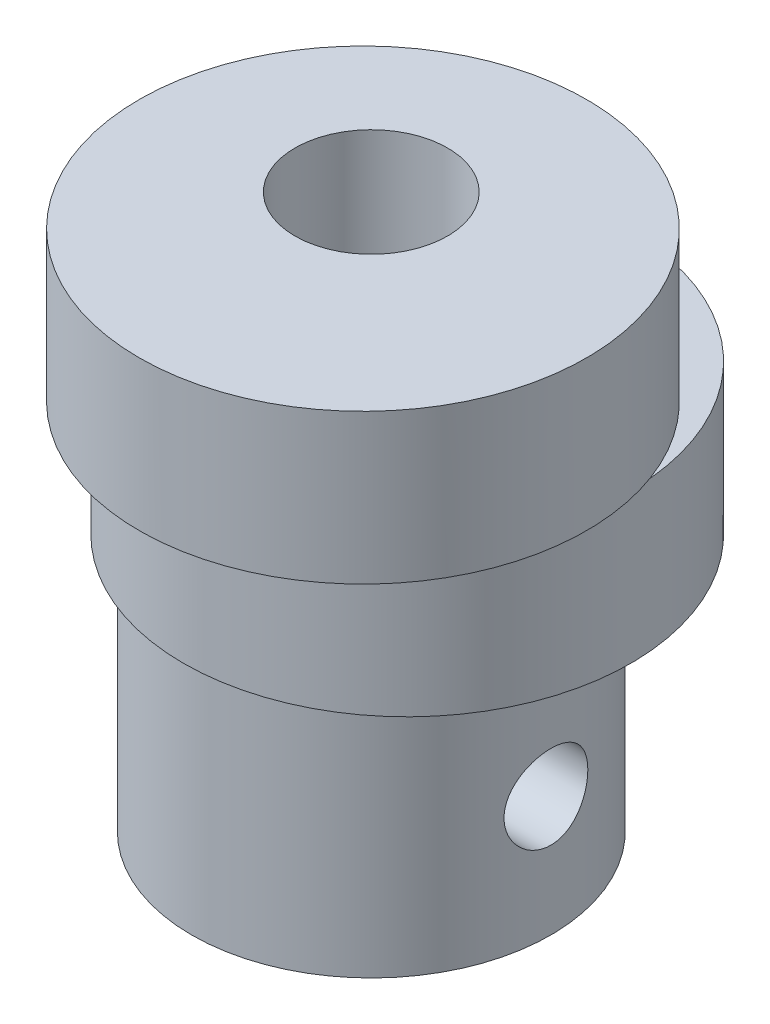
SolidWorks part; units mm, degrees
ref_plane "Front Plane" through (0, 0, 0) normal (0, 0, 1) x (1, 0, 0)
ref_plane "Top Plane" through (0, 0, 0) normal (0, 1, 0) x (1, 0, 0)
ref_plane "Right Plane" through (0, 0, 0) normal (1, 0, 0) x (0, 0, -1)
sketch "Sketch2" plane through (0, 0, 0) normal (0, 1, 0) x (1, 0, 0)
  circle A0 centre (0, 0) radius 6
  dimension "D1" = 12
extrude "Base" add sketch "Sketch2" along normal blind 8
sketch "Sketch3" plane through (0, 8, 0) normal (0, 1, 0) x (1, 0, 0)
  circle A0 centre (0, 1.2) radius 7.475
  dimension "D1" = 14.95
  dimension "D2" = 1.2
extrude "Cam A" add sketch "Sketch3" along normal blind 5
sketch "Sketch4" plane through (0, 13, 0) normal (0, 1, 0) x (1, 0, 0)
  circle A0 centre (0, 0) radius 6
  dimension "D1" = 12
extrude "Spacer" add sketch "Sketch4" along normal blind 0.5
sketch "Sketch5" plane through (0, 13.5, 0) normal (0, 1, 0) x (1, 0, 0)
  circle A0 centre (0.9213, -1.2) radius 7.475
  dimension "D1" = 14.95
  dimension "D2" = 1.2
extrude "Cam B" add sketch "Sketch5" along normal blind 5
sketch "Sketch6" plane through (0, 18.5, 0) normal (0, 1, 0) x (1, 0, 0)
  circle A0 centre (0, 0) radius 2.55
  dimension "D1" = 5.1
extrude "Shaft Hole" cut sketch "Sketch6" against normal through all
sketch "Sketch7" plane through (0, 0, 0) normal (1, 0, 0) x (0, 0, -1)
  circle A0 centre (0, 4) radius 1.4
  dimension "D1" = 2.8
  dimension "D2" = 4
extrude "Screw Holes" cut sketch "Sketch7" against normal through all and the other way through all
